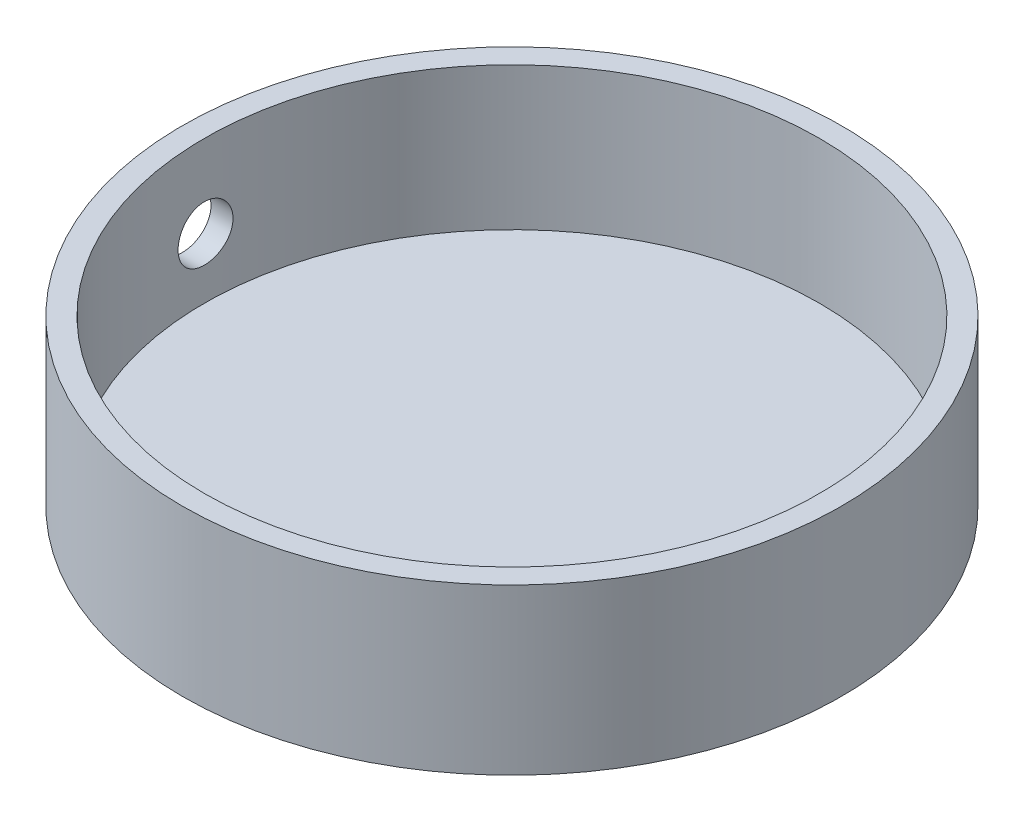
SolidWorks part; units mm, degrees
ref_plane "Front Plane" through (0, 0, 0) normal (0, 0, 1) x (1, 0, 0)
ref_plane "Top Plane" through (0, 0, 0) normal (0, 1, 0) x (1, 0, 0)
ref_plane "Right Plane" through (0, 0, 0) normal (1, 0, 0) x (0, 0, -1)
sketch "Sketch1" plane through (0, 0, 0) normal (0, 1, 0) x (1, 0, 0)
  circle A0 centre (0, 0) radius 38.1
  dimension "D1" = 76.2
extrude "Boss-Extrude1" add sketch "Sketch1" along normal blind 2.54
sketch "Sketch2" plane through (0, 2.54, 0) normal (0, 1, 0) x (1, 0, 0)
  circle A0 centre (0, 0) radius 38.1
  circle A1 centre (0, 0) radius 35.56
  circle A2 centre (0, 0) radius 38.1 construction
  dimension "D1" = 2.54
extrude "Boss-Extrude2" add sketch "Sketch2" along normal blind 16.51
ref_plane "Plane1" through (-38.1, 0, 0) normal (-1, 0, 0) x (0, 0, 1)
sketch "Sketch3" plane through (-38.1, 0, 0) normal (-1, 0, 0) x (0, 0, 1)
  line L0 (0, 19.05) -> (0, 0) construction
  line L1 (38.1, 19.05) -> (-38.1, 19.05) construction
  circle A0 centre (0, 9.525) radius 3.175
  point P7 (0, 10.5834)
  dimension "D1" = 6.35
extrude "Cut-Extrude1" cut sketch "Sketch3" against normal up to surface (2.682 mm away)
